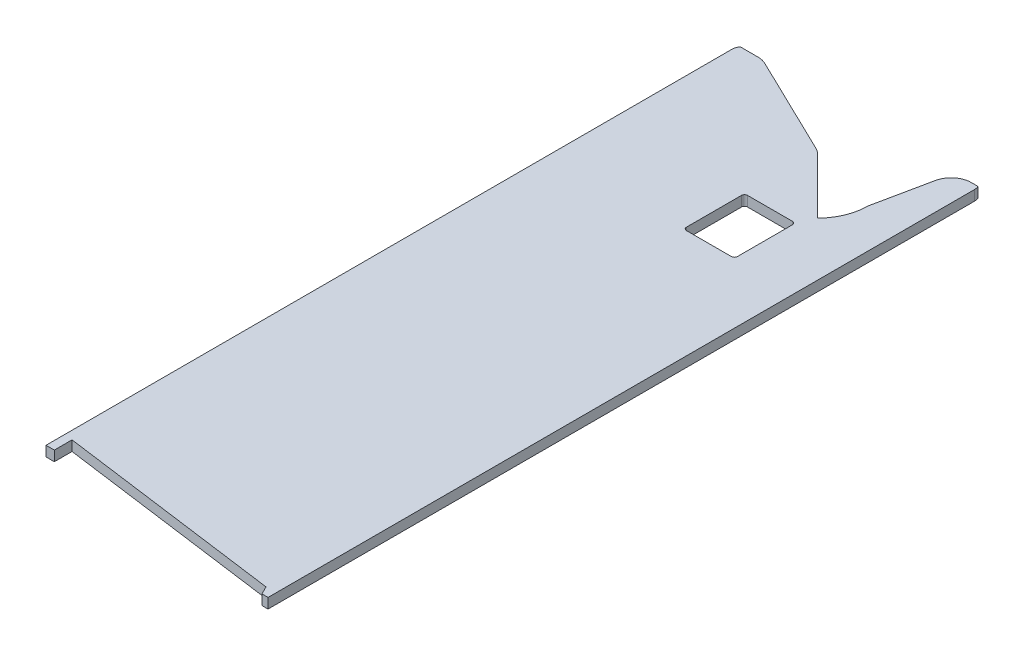
SolidWorks part; units mm, degrees
material "Yellow Foam"
ref_plane "Front Plane" through (0, 0, 0) normal (0, 0, 1) x (1, 0, 0)
ref_plane "Top Plane" through (0, 0, 0) normal (0, 1, 0) x (1, 0, 0)
ref_plane "Right Plane" through (0, 0, 0) normal (1, 0, 0) x (0, 0, -1)
sketch "Sketch1" plane through (0, 0, 0) normal (0, 1, 0) x (1, 0, 0)
  line L1 (304.8, 914.4) -> (-304.8, 914.4)
  line L2 (304.8, 914.4) -> (304.8, -914.4)
  line L3 (304.8, -914.4) -> (-304.8, -914.4)
  line L4 (-304.8, 914.4) -> (-304.8, -914.4)
  line L5 (304.8, 914.4) -> (-304.8, -914.4) construction
  line L6 (304.8, -914.4) -> (-304.8, 914.4) construction
  point P0 (0, 0)
  dimension "D1" = 609.6
  dimension "D2" = 1828.8
extrude "Boss-Extrude1" add sketch "Sketch1" along normal blind 25.4
fillet "Fillet1" radius 25.4 4 edges at (-304.8, 12.7, -914.4) (304.8, 12.7, -914.4) (304.8, 12.7, 914.4) (-304.8, 12.7, 914.4)
sketch "Sketch3" plane through (0, 25.4, 0) normal (0, 1, 0) x (1, 0, 0)
  line L2 (16.2516, 779.1931) -> (-233.1475, 899.8431)
  line L3 (-255.27, 904.9131) -> (-323.85, 904.9131)
  line L6 (92.701, 706.7332) -> (170.1299, 629.3043)
  line L7 (170.1299, 808.8314) -> (92.701, 731.4025)
  line L8 (30.0501, 769.3841) -> (170.1299, 629.3043)
  line L10 (-323.85, 904.9131) -> (-323.85, 931.5931)
  line L11 (-323.85, 931.5931) -> (311.15, 931.5931)
  line L12 (311.15, 931.5931) -> (311.15, 899.8431)
  line L13 (311.15, 899.8431) -> (285.75, 899.8431)
  line L14 (236.0165, 859.3979) -> (207.8241, 723.9921)
  arc A4 (-233.1475, 899.8431) -> (-255.27, 904.9131) centre (-255.27, 854.1131) ccw
  arc A5 (285.75, 899.8431) -> (236.0165, 859.3979) centre (285.75, 849.0431) ccw
  arc A8 (92.701, 706.7332) -> (92.701, 731.4025) centre (78.74, 719.0679) ccw
  arc A9 (170.1299, 629.3043) -> (170.1299, 808.8314) centre (78.74, 719.0679) ccw
  arc A11 (170.1299, 629.3043) -> (206.781, 715.1793) centre (78.74, 719.0679) ccw
  arc A12 (16.2516, 779.1931) -> (30.0501, 769.3841) centre (-5.8709, 733.4631) cw
  arc A13 (207.8241, 723.9921) -> (206.781, 715.1793) centre (257.5576, 713.6372) ccw
  dimension "D1" = 6.35
  dimension "D2" = 50.8
  dimension "D3" = 50.8
  dimension "D4" = 50.8
  dimension "D11" = 50.8
  dimension "D5" = 152.4
  dimension "D6" = 31.75
  dimension "D7" = 635
  dimension "D8" = 931.5931
  dimension "D9" = 311.15
  dimension "D10" = 31.75
  dimension "D12" = 68.58
  dimension "D13" = 25.4
  dimension "D14" = 103.3259
extrude "Cut-Extrude2" cut sketch "Sketch3" against normal through all
sketch "Sketch4" plane through (0, 25.4, 0) normal (0, 1, 0) x (1, 0, 0)
  line L0 (-327.07, -833.12) -> (-283.89, -833.12)
  line L1 (-283.89, -833.12) -> (-283.89, -788.67)
  line L2 (-283.89, -788.67) -> (279.4, -864.87)
  line L3 (279.4, -864.87) -> (289.56, -885.19)
  line L4 (289.56, -885.19) -> (330.2, -885.19)
  line L5 (330.2, -885.19) -> (330.2, -946.15)
  line L6 (330.2, -946.15) -> (-327.07, -946.15)
  line L7 (-327.07, -946.15) -> (-327.07, -833.12)
  dimension "D1" = 946.15
  dimension "D2" = 330.2
  dimension "D3" = 60.96
  dimension "D4" = 40.64
  dimension "D5" = 81.28
  dimension "D6" = 157.48
  dimension "D7" = 113.03
  dimension "D8" = 43.18
  dimension "D9" = 50.8
  dimension "D10" = 614.09
extrude "Cut-Extrude3" cut sketch "Sketch4" against normal through all
sketch "Sketch5" plane through (0, 0, 0) normal (0, -1, 0) x (1, 0, 0)
  line L0 (152.8434, -583.3745) -> (152.8434, -445.3255) construction
  line L1 (145.2245, -437.7066) -> (32.5755, -437.7066) construction
  line L2 (24.9566, -445.3255) -> (24.9566, -583.3745) construction
  line L3 (32.5755, -590.9934) -> (145.2245, -590.9934) construction
  line L4 (152.8434, -583.3745) -> (152.8434, -445.3255)
  line L5 (145.2245, -437.7066) -> (32.5755, -437.7066)
  line L6 (24.9566, -445.3255) -> (24.9566, -583.3745)
  line L7 (32.5755, -590.9934) -> (145.2245, -590.9934)
  ellipse E0 centre (145.2222, -583.3722) end of major axis (139.8324, -577.9824) minor radius 7.62 (145.2245, -590.9934) -> (152.8434, -583.3745) ccw construction
  ellipse E1 centre (145.2222, -445.3278) end of major axis (139.8324, -450.7176) minor radius 7.62 (152.8434, -445.3255) -> (145.2245, -437.7066) ccw construction
  ellipse E2 centre (32.5778, -445.3278) end of major axis (37.9676, -450.7176) minor radius 7.62 (32.5755, -437.7066) -> (24.9566, -445.3255) ccw construction
  ellipse E3 centre (32.5778, -583.3722) end of major axis (37.9676, -577.9824) minor radius 7.62 (24.9566, -583.3745) -> (32.5755, -590.9934) ccw construction
  ellipse E4 centre (145.2222, -583.3722) end of major axis (139.8324, -577.9824) minor radius 7.62 (145.2245, -590.9934) -> (152.8434, -583.3745) ccw
  ellipse E5 centre (145.2222, -445.3278) end of major axis (139.8324, -450.7176) minor radius 7.62 (152.8434, -445.3255) -> (145.2245, -437.7066) ccw
  ellipse E6 centre (32.5778, -445.3278) end of major axis (37.9676, -450.7176) minor radius 7.62 (32.5755, -437.7066) -> (24.9566, -445.3255) ccw
  ellipse E7 centre (32.5778, -583.3722) end of major axis (37.9676, -577.9824) minor radius 7.62 (24.9566, -583.3745) -> (32.5755, -590.9934) ccw
extrude "Cut-Extrude4" cut sketch "Sketch5" against normal through all
